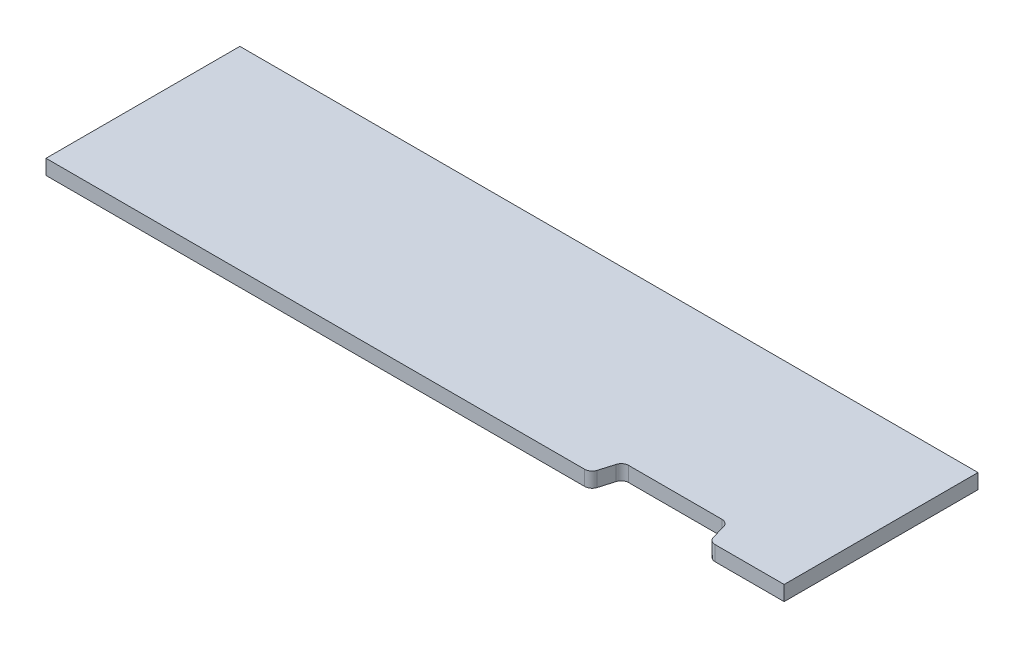
SolidWorks part; units mm, degrees
ref_plane "Front Plane" through (0, 0, 0) normal (0, 0, 1) x (1, 0, 0)
ref_plane "Top Plane" through (0, 0, 0) normal (0, 1, 0) x (1, 0, 0)
ref_plane "Right Plane" through (0, 0, 0) normal (1, 0, 0) x (0, 0, -1)
sketch "Sketch1" plane through (0, 0, 0) normal (0, 1, 0) x (1, 0, 0)
  line L1 (-314.325, -82.55) -> (314.325, -82.55)
  line L2 (-314.325, -82.55) -> (-314.325, 82.55)
  line L3 (-314.325, 82.55) -> (314.325, 82.55)
  line L4 (314.325, -82.55) -> (314.325, 82.55)
  line L5 (-314.325, -82.55) -> (314.325, 82.55) construction
  line L6 (-314.325, 82.55) -> (314.325, -82.55) construction
  point P0 (0, 0)
  dimension "D1" = 165.1
  dimension "D2" = 628.65
extrude "Boss-Extrude1" add sketch "Sketch1" along normal blind 12.7
sketch "Sketch2" plane through (0, 0, 0) normal (0, -1, 0) x (1, 0, 0)
  line L0 (149.225, 82.55) -> (250.825, 82.55)
  line L1 (-314.325, 82.55) -> (314.325, 82.55) construction
  line L2 (250.825, 82.55) -> (244.475, 60.96)
  line L3 (244.475, 60.96) -> (155.575, 60.96)
  line L4 (155.575, 60.96) -> (149.225, 82.55)
  line L5 (200.025, 60.96) -> (200.025, 82.55) construction
  dimension "D1" = 21.59
  dimension "D2" = 63.5
  dimension "D3" = 88.9
  dimension "D4" = 101.6
extrude "Cut-Extrude1" cut sketch "Sketch2" against normal blind 12.7
fillet "Fillet1" radius 6.35 4 edges at (250.825, 6.35, 82.55) (244.475, 6.35, 60.96) (155.575, 6.35, 60.96) (149.225, 6.35, 82.55)
